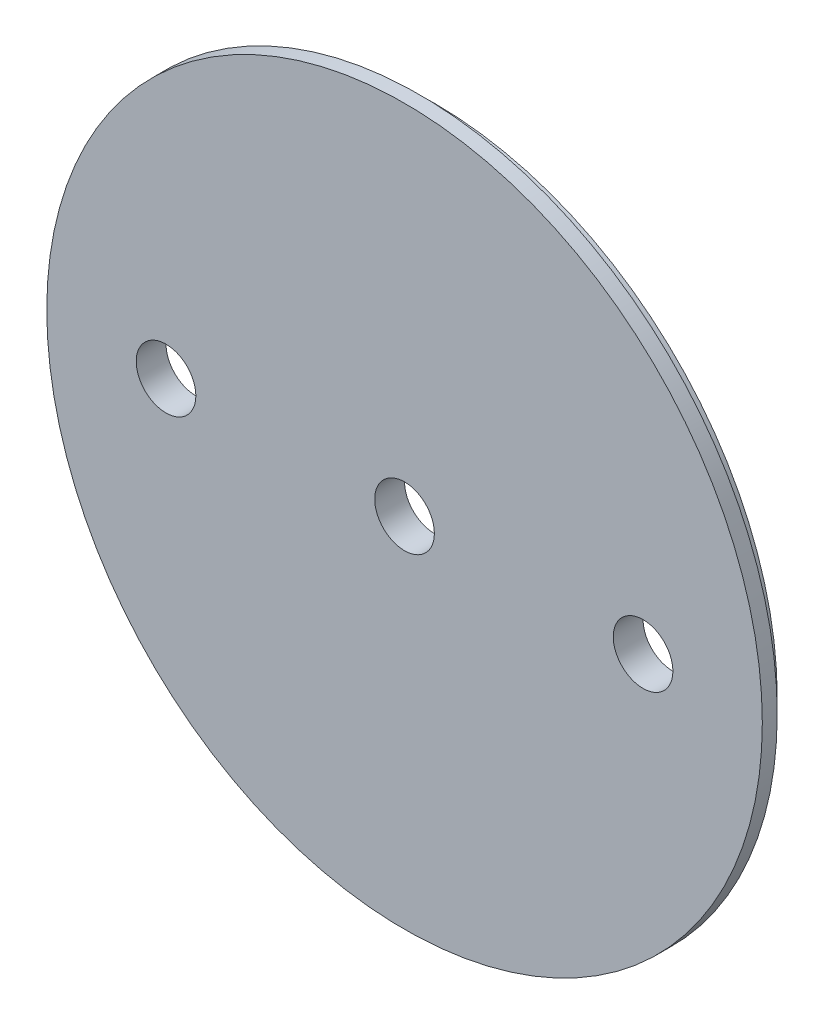
SolidWorks part; units mm, degrees
ref_plane "Front Plane" through (0, 0, 0) normal (0, 0, 1) x (1, 0, 0)
ref_plane "Top Plane" through (0, 0, 0) normal (0, 1, 0) x (1, 0, 0)
ref_plane "Right Plane" through (0, 0, 0) normal (1, 0, 0) x (0, 0, -1)
sketch "Sketch1" plane through (0, 0, 0) normal (0, 0, 1) x (1, 0, 0)
  circle A0 centre (0, 0) radius 38.1
  dimension "D1" = 76.2
extrude "Boss-Extrude1" add sketch "Sketch1" along normal blind 3.175 contours A0
sketch "Sketch2" plane through (0, 0, 0) normal (0, 0, -1) x (-1, 0, 0)
  circle A0 centre (0, 0) radius 36.5125
  circle A1 centre (0, 0) radius 36.5125
  circle A2 centre (0, 0) radius 38.1
  dimension "D1" = 73.025
extrude "Cut-Extrude1" cut sketch "Sketch2" against normal blind 1.5875 contours A0 | A2
sketch "Sketch3" plane through (0, 0, 3.175) normal (0, 0, 1) x (1, 0, 0)
  circle A0 centre (0, 0) radius 3.175
  circle A1 centre (25.4, 0) radius 3.175
  circle A2 centre (-25.4, 0) radius 3.175
  dimension "D1" = 6.35
  dimension "D2" = 25.4
  dimension "D3" = 25.4
extrude "Cut-Extrude2" cut sketch "Sketch3" against normal through all
